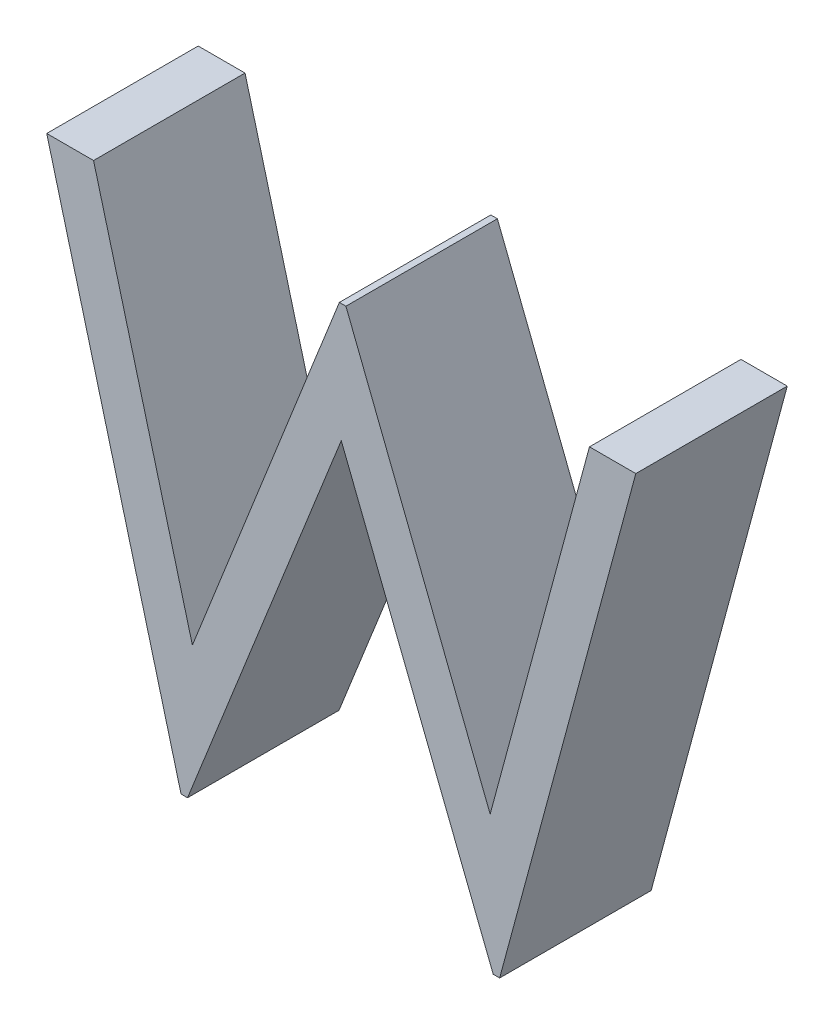
SolidWorks part; units mm, degrees
ref_plane "Plan de face" through (0, 0, 0) normal (0, 0, 1) x (1, 0, 0)
ref_plane "Plan de dessus" through (0, 0, 0) normal (0, 1, 0) x (1, 0, 0)
ref_plane "Plan de droite" through (0, 0, 0) normal (1, 0, 0) x (0, 0, -1)
sketch "Esquisse1" plane through (0, 0, 0) normal (0, 0, 1) x (1, 0, 0)
  text T0 "W" font "Century Gothic" height 5
extrude "Boss.-Extru.1" add sketch "Esquisse1" along normal blind 1.5
